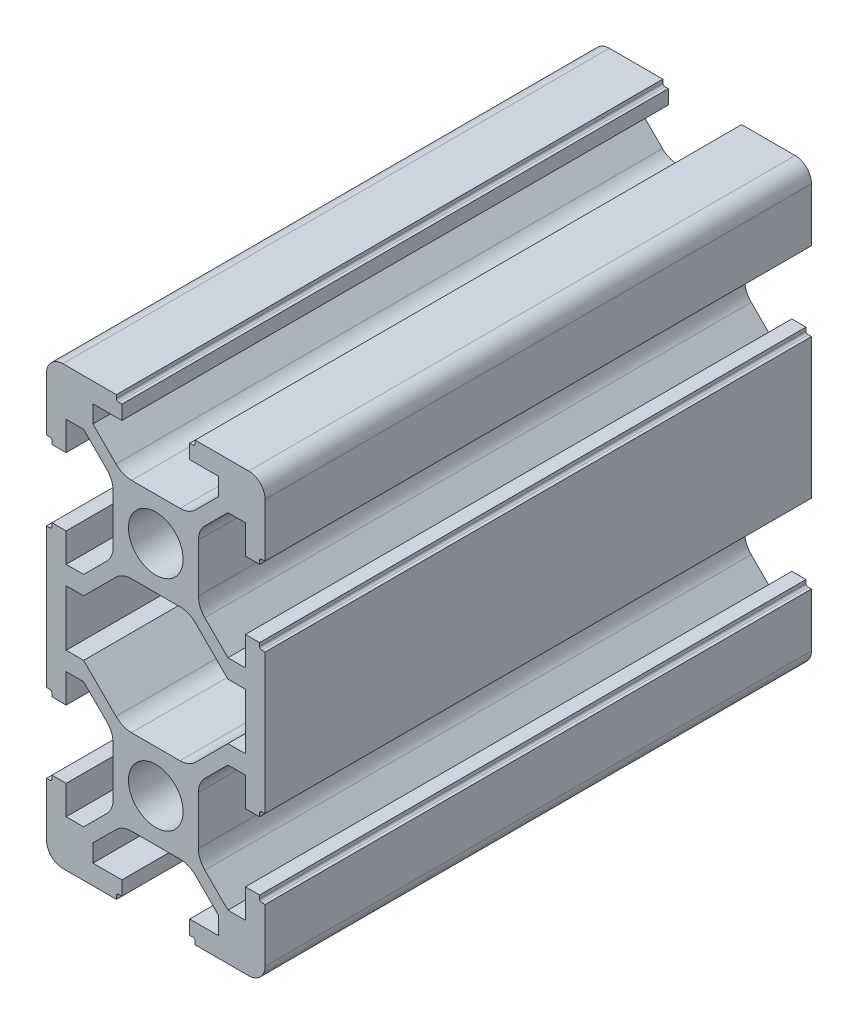
SolidWorks part; units mm, degrees
ref_plane "Alzado" through (0, 0, 0) normal (0, 0, 1) x (1, 0, 0)
ref_plane "Planta" through (0, 0, 0) normal (0, 1, 0) x (1, 0, 0)
ref_plane "Vista lateral" through (0, 0, 0) normal (1, 0, 0) x (0, 0, -1)
sketch "Croquis1" plane through (0, 0, 0) normal (0, 0, 1) x (1, 0, 0)
  line L0 (0, 0) -> (-10, -10) construction
  line L32 (0, 0) -> (-3.9, 0) construction
  line L58 (0, 0) -> (0, -3.9) construction
  line L60 (-4.4858, -3.6373) -> (-6.6, -5.7515)
  line L61 (-6.6, -5.7515) -> (-8.2, -5.7515)
  line L110 (-8.2, -5.7515) -> (-8.2, -3.1)
  line L111 (-8.2, -3.1) -> (-9.5, -3.1)
  line L112 (-9.5, -3.1) -> (-9.5, -3.4)
  line L113 (-9.7, -3.6) -> (-10, -3.6)
  line L114 (-10, -3.6) -> (-10, -8.5)
  line L115 (-3.6373, -4.4858) -> (-5.7515, -6.6)
  line L116 (-5.7515, -6.6) -> (-5.7515, -8.2)
  line L117 (-3.1, -8.2) -> (-3.1, -9.5)
  line L118 (-5.7515, -8.2) -> (-3.1, -8.2)
  line L119 (-3.1, -9.5) -> (-3.4, -9.5)
  line L120 (-3.6, -9.7) -> (-3.6, -10)
  line L121 (-3.6, -10) -> (-8.5, -10)
  line L122 (9.7, -3.6) -> (10, -3.6)
  line L123 (9.5, -3.1) -> (9.5, -3.4)
  line L124 (8.2, -3.1) -> (9.5, -3.1)
  line L125 (3.6, -10) -> (8.5, -10)
  line L126 (3.6, -9.7) -> (3.6, -10)
  line L127 (3.1, -9.5) -> (3.4, -9.5)
  line L128 (5.7515, -8.2) -> (3.1, -8.2)
  line L129 (3.1, -8.2) -> (3.1, -9.5)
  line L130 (5.7515, -6.6) -> (5.7515, -8.2)
  line L131 (3.6373, -4.4858) -> (5.7515, -6.6)
  line L132 (10, -3.6) -> (10, -8.5)
  line L133 (8.2, -5.7515) -> (8.2, -3.1)
  line L134 (6.6, -5.7515) -> (8.2, -5.7515)
  line L135 (4.4858, -3.6373) -> (6.6, -5.7515)
  line L136 (5.7515, 8.2) -> (3.1, 8.2)
  line L137 (3.6, 10) -> (8.5, 10)
  line L138 (-9.7, 3.6) -> (-10, 3.6)
  line L139 (-9.5, 3.1) -> (-9.5, 3.4)
  line L140 (-8.2, 3.1) -> (-9.5, 3.1)
  line L141 (-8.2, 5.7515) -> (-8.2, 3.1)
  line L142 (-6.6, 5.7515) -> (-8.2, 5.7515)
  line L143 (-4.4858, 3.6373) -> (-6.6, 5.7515)
  line L144 (3.1, 8.2) -> (3.1, 9.5)
  line L145 (3.1, 9.5) -> (3.4, 9.5)
  line L146 (3.6, 9.7) -> (3.6, 10)
  line L147 (-3.6, 10) -> (-8.5, 10)
  line L148 (-3.6, 9.7) -> (-3.6, 10)
  line L149 (-3.1, 9.5) -> (-3.4, 9.5)
  line L150 (-5.7515, 8.2) -> (-3.1, 8.2)
  line L151 (-3.1, 8.2) -> (-3.1, 9.5)
  line L152 (-5.7515, 6.6) -> (-5.7515, 8.2)
  line L153 (-3.6373, 4.4858) -> (-5.7515, 6.6)
  line L154 (-10, 3.6) -> (-10, 8.5)
  line L155 (4.4858, 3.6373) -> (6.6, 5.7515)
  line L156 (6.6, 5.7515) -> (8.2, 5.7515)
  line L157 (8.2, 5.7515) -> (8.2, 3.1)
  line L158 (10, 3.6) -> (10, 8.5)
  line L159 (3.6373, 4.4858) -> (5.7515, 6.6)
  line L160 (5.7515, 6.6) -> (5.7515, 8.2)
  line L161 (8.2, 3.1) -> (9.5, 3.1)
  line L162 (9.5, 3.1) -> (9.5, 3.4)
  line L163 (9.7, 3.6) -> (10, 3.6)
  line L164 (-3.9, 2.223) -> (-3.9, -2.223)
  line L165 (-2.223, -3.9) -> (2.223, -3.9)
  line L166 (3.9, -2.223) -> (3.9, 2.223)
  line L167 (2.223, 3.9) -> (-2.223, 3.9)
  circle A2 centre (0, 0) radius 2.5
  arc A3 (8.5, -10) -> (10, -8.5) centre (8.5, -8.5) ccw
  arc A4 (8.5, 10) -> (10, 8.5) centre (8.5, 8.5) cw
  arc A5 (-8.5, 10) -> (-10, 8.5) centre (-8.5, 8.5) ccw
  arc A6 (-10, -8.5) -> (-8.5, -10) centre (-8.5, -8.5) ccw
  arc A7 (-3.9, -2.223) -> (-4.4858, -3.6373) centre (-5.9, -2.223) cw
  arc A8 (4.4858, -3.6373) -> (3.9, -2.223) centre (5.9, -2.223) cw
  arc A9 (4.4858, 3.6373) -> (3.9, 2.223) centre (5.9, 2.223) ccw
  arc A10 (3.6373, 4.4858) -> (2.223, 3.9) centre (2.223, 5.9) cw
  arc A11 (-3.6373, 4.4858) -> (-2.223, 3.9) centre (-2.223, 5.9) ccw
  arc A12 (-4.4858, 3.6373) -> (-3.9, 2.223) centre (-5.9, 2.223) cw
  arc A13 (3.6373, -4.4858) -> (2.223, -3.9) centre (2.223, -5.9) ccw
  arc A14 (-3.6373, -4.4858) -> (-2.223, -3.9) centre (-2.223, -5.9) cw
  arc A15 (-3.4, -9.5) -> (-3.6, -9.7) centre (-3.4, -9.7) ccw
  arc A16 (3.6, -9.7) -> (3.4, -9.5) centre (3.4, -9.7) ccw
  arc A17 (9.7, -3.6) -> (9.5, -3.4) centre (9.7, -3.4) cw
  arc A18 (9.5, 3.4) -> (9.7, 3.6) centre (9.7, 3.4) cw
  arc A19 (3.4, 9.5) -> (3.6, 9.7) centre (3.4, 9.7) ccw
  arc A20 (-9.7, 3.6) -> (-9.5, 3.4) centre (-9.7, 3.4) cw
  arc A21 (-3.6, 9.7) -> (-3.4, 9.5) centre (-3.4, 9.7) ccw
  arc A22 (-9.5, -3.4) -> (-9.7, -3.6) centre (-9.7, -3.4) cw
  point P0 (0, 0)
  point P22 (10, -10)
  point P78 (10, 10)
  point P81 (-10, 10)
  point P90 (-3.9, -3.0515)
  point P93 (3.9, -3.0515)
  point P96 (3.9, 3.0515)
  point P99 (3.0515, 3.9)
  point P102 (-3.0515, 3.9)
  point P105 (-3.9, 3.0515)
  point P108 (3.0515, -3.9)
  point P111 (-3.0515, -3.9)
  point P116 (-3.6, -9.5)
  point P119 (3.6, -9.5)
  point P122 (9.5, -3.6)
  point P125 (9.5, 3.6)
  point P128 (3.6, 9.5)
  point P131 (-9.5, 3.6)
  point P134 (-3.6, 9.5)
  point P137 (-9.5, -3.6)
  dimension "D10" = 20
  dimension "D1" = 5
  dimension "D11" = 1.5
  dimension "D13" = 2
  dimension "D15" = 0.2
  dimension "D2" = 6.2
  dimension "D3" = 7.2
  dimension "D4" = 0.5
  dimension "D5" = 3.4
  dimension "D6" = 11.5029
  dimension "D7" = 6.1
  dimension "D8" = 1.8
  dimension "D9" = 1.2
extrude "Saliente-Extruir1" [suppressed] add sketch "Croquis1" along normal mid plane 100
sketch "Croquis3" plane through (0, 0, 0) normal (0, 0, 1) x (1, 0, 0)
  line L0 (-3.6363, -5.5152) -> (-6.6, -2.5556)
  line L3 (0, 0) -> (-10, 0) construction
  line L5 (-6.6, -2.5556) -> (-8.2, -2.5556)
  line L7 (0, -13.9) -> (0, -6.1) construction
  line L56 (-9.5, -13.1015) -> (-9.5, -13.4015)
  line L57 (-8.2, -13.1015) -> (-9.5, -13.1015)
  line L58 (-8.2, -15.7515) -> (-8.2, -13.1015)
  line L59 (-6.6, -15.7515) -> (-8.2, -15.7515)
  line L60 (-4.4858, -13.6373) -> (-6.6, -15.7515)
  line L61 (-3.9, -7.777) -> (-3.9, -12.223)
  line L62 (-6.6, -4.2515) -> (-4.4868, -6.3618)
  line L63 (-8.2, -4.2515) -> (-6.6, -4.2515)
  line L64 (-8.2, -6.9015) -> (-8.2, -4.2515)
  line L65 (-9.5, -6.9015) -> (-8.2, -6.9015)
  line L66 (-9.5, -6.6015) -> (-9.5, -6.9015)
  line L67 (-10, -6.4015) -> (-9.7, -6.4015)
  line L68 (-5.7515, -16.6) -> (-3.6373, -14.4858)
  line L69 (-5.7515, -18.2) -> (-5.7515, -16.6)
  line L70 (-3.1015, -18.2) -> (-5.7515, -18.2)
  line L71 (-3.1015, -19.5) -> (-3.1015, -18.2)
  line L72 (-3.4015, -19.5) -> (-3.1015, -19.5)
  line L73 (-3.6015, -20) -> (-3.6015, -19.7)
  line L74 (-8.5, -20) -> (-3.6015, -20)
  line L75 (-10, -13.6015) -> (-10, -18.5)
  line L76 (-9.7, -13.6015) -> (-10, -13.6015)
  line L102 (-10, -6.4015) -> (-10, 6.4015)
  line L103 (-8.2, -2.5556) -> (-8.2, 2.5556)
  line L104 (-2.223, -6.1) -> (2.223, -6.1)
  line L105 (-2.223, -13.9) -> (2.223, -13.9)
  line L106 (8.2, -2.5556) -> (8.2, 2.5556)
  line L107 (10, -6.4015) -> (10, 6.4015)
  line L108 (9.7, -13.6015) -> (10, -13.6015)
  line L109 (10, -13.6015) -> (10, -18.5)
  line L110 (8.5, -20) -> (3.6015, -20)
  line L111 (3.6015, -20) -> (3.6015, -19.7)
  line L112 (3.4015, -19.5) -> (3.1015, -19.5)
  line L113 (3.1015, -19.5) -> (3.1015, -18.2)
  line L114 (3.1015, -18.2) -> (5.7515, -18.2)
  line L115 (5.7515, -18.2) -> (5.7515, -16.6)
  line L116 (5.7515, -16.6) -> (3.6373, -14.4858)
  line L117 (10, -6.4015) -> (9.7, -6.4015)
  line L118 (9.5, -6.6015) -> (9.5, -6.9015)
  line L119 (9.5, -6.9015) -> (8.2, -6.9015)
  line L120 (8.2, -6.9015) -> (8.2, -4.2515)
  line L121 (8.2, -4.2515) -> (6.6, -4.2515)
  line L122 (6.6, -4.2515) -> (4.4868, -6.3618)
  line L123 (3.9, -7.777) -> (3.9, -12.223)
  line L124 (4.4858, -13.6373) -> (6.6, -15.7515)
  line L125 (6.6, -15.7515) -> (8.2, -15.7515)
  line L126 (8.2, -15.7515) -> (8.2, -13.1015)
  line L127 (8.2, -13.1015) -> (9.5, -13.1015)
  line L128 (9.5, -13.1015) -> (9.5, -13.4015)
  line L129 (6.6, -2.5556) -> (8.2, -2.5556)
  line L130 (3.6363, -5.5152) -> (6.6, -2.5556)
  line L131 (3.6363, 5.5152) -> (6.6, 2.5556)
  line L132 (6.6, 2.5556) -> (8.2, 2.5556)
  line L133 (9.5, 13.1015) -> (9.5, 13.4015)
  line L134 (8.2, 13.1015) -> (9.5, 13.1015)
  line L135 (8.2, 15.7515) -> (8.2, 13.1015)
  line L136 (6.6, 15.7515) -> (8.2, 15.7515)
  line L137 (4.4858, 13.6373) -> (6.6, 15.7515)
  line L138 (3.9, 7.777) -> (3.9, 12.223)
  line L139 (6.6, 4.2515) -> (4.4868, 6.3618)
  line L140 (8.2, 4.2515) -> (6.6, 4.2515)
  line L141 (8.2, 6.9015) -> (8.2, 4.2515)
  line L142 (9.5, 6.9015) -> (8.2, 6.9015)
  line L143 (9.5, 6.6015) -> (9.5, 6.9015)
  line L144 (10, 6.4015) -> (9.7, 6.4015)
  line L145 (5.7515, 16.6) -> (3.6373, 14.4858)
  line L146 (5.7515, 18.2) -> (5.7515, 16.6)
  line L147 (3.1015, 18.2) -> (5.7515, 18.2)
  line L148 (3.1015, 19.5) -> (3.1015, 18.2)
  line L149 (3.4015, 19.5) -> (3.1015, 19.5)
  line L150 (3.6015, 20) -> (3.6015, 19.7)
  line L151 (8.5, 20) -> (3.6015, 20)
  line L152 (10, 13.6015) -> (10, 18.5)
  line L153 (9.7, 13.6015) -> (10, 13.6015)
  line L154 (-2.223, 13.9) -> (2.223, 13.9)
  line L155 (-2.223, 6.1) -> (2.223, 6.1)
  line L156 (-9.7, 13.6015) -> (-10, 13.6015)
  line L157 (-10, 13.6015) -> (-10, 18.5)
  line L158 (-8.5, 20) -> (-3.6015, 20)
  line L159 (-3.6015, 20) -> (-3.6015, 19.7)
  line L160 (-3.4015, 19.5) -> (-3.1015, 19.5)
  line L161 (-3.1015, 19.5) -> (-3.1015, 18.2)
  line L162 (-3.1015, 18.2) -> (-5.7515, 18.2)
  line L163 (-5.7515, 18.2) -> (-5.7515, 16.6)
  line L164 (-5.7515, 16.6) -> (-3.6373, 14.4858)
  line L165 (-10, 6.4015) -> (-9.7, 6.4015)
  line L166 (-9.5, 6.6015) -> (-9.5, 6.9015)
  line L167 (-9.5, 6.9015) -> (-8.2, 6.9015)
  line L168 (-8.2, 6.9015) -> (-8.2, 4.2515)
  line L169 (-8.2, 4.2515) -> (-6.6, 4.2515)
  line L170 (-6.6, 4.2515) -> (-4.4868, 6.3618)
  line L171 (-3.9, 7.777) -> (-3.9, 12.223)
  line L172 (-4.4858, 13.6373) -> (-6.6, 15.7515)
  line L173 (-6.6, 15.7515) -> (-8.2, 15.7515)
  line L174 (-8.2, 15.7515) -> (-8.2, 13.1015)
  line L175 (-8.2, 13.1015) -> (-9.5, 13.1015)
  line L176 (-9.5, 13.1015) -> (-9.5, 13.4015)
  line L177 (-6.6, 2.5556) -> (-8.2, 2.5556)
  line L178 (-3.6363, 5.5152) -> (-6.6, 2.5556)
  line L179 (0, -10) -> (-9.5607, -19.5607) construction
  circle A8 centre (0, -10) radius 2.5
  arc A20 (-4.4858, -13.6373) -> (-3.9, -12.223) centre (-5.9, -12.223) ccw
  arc A21 (-3.9, -7.777) -> (-4.4868, -6.3618) centre (-5.9, -7.777) ccw
  arc A22 (-9.5, -6.6015) -> (-9.7, -6.4015) centre (-9.7, -6.6015) ccw
  arc A23 (-3.6363, -5.5152) -> (-2.223, -6.1) centre (-2.223, -4.1) ccw
  arc A24 (-2.223, -13.9) -> (-3.6373, -14.4858) centre (-2.223, -15.9) ccw
  arc A25 (-3.4015, -19.5) -> (-3.6015, -19.7) centre (-3.4015, -19.7) ccw
  arc A26 (-10, -18.5) -> (-8.5, -20) centre (-8.5, -18.5) ccw
  arc A27 (-9.7, -13.6015) -> (-9.5, -13.4015) centre (-9.7, -13.4015) ccw
  arc A34 (9.7, -13.6015) -> (9.5, -13.4015) centre (9.7, -13.4015) cw
  arc A35 (10, -18.5) -> (8.5, -20) centre (8.5, -18.5) cw
  arc A36 (3.4015, -19.5) -> (3.6015, -19.7) centre (3.4015, -19.7) cw
  arc A37 (2.223, -13.9) -> (3.6373, -14.4858) centre (2.223, -15.9) cw
  arc A38 (3.6363, -5.5152) -> (2.223, -6.1) centre (2.223, -4.1) cw
  arc A39 (9.5, -6.6015) -> (9.7, -6.4015) centre (9.7, -6.6015) cw
  arc A40 (3.9, -7.777) -> (4.4868, -6.3618) centre (5.9, -7.777) cw
  arc A41 (4.4858, -13.6373) -> (3.9, -12.223) centre (5.9, -12.223) cw
  arc A42 (4.4858, 13.6373) -> (3.9, 12.223) centre (5.9, 12.223) ccw
  arc A43 (3.9, 7.777) -> (4.4868, 6.3618) centre (5.9, 7.777) ccw
  arc A44 (9.5, 6.6015) -> (9.7, 6.4015) centre (9.7, 6.6015) ccw
  arc A45 (3.6363, 5.5152) -> (2.223, 6.1) centre (2.223, 4.1) ccw
  arc A46 (2.223, 13.9) -> (3.6373, 14.4858) centre (2.223, 15.9) ccw
  arc A47 (3.4015, 19.5) -> (3.6015, 19.7) centre (3.4015, 19.7) ccw
  arc A48 (10, 18.5) -> (8.5, 20) centre (8.5, 18.5) ccw
  arc A49 (9.7, 13.6015) -> (9.5, 13.4015) centre (9.7, 13.4015) ccw
  arc A50 (-9.7, 13.6015) -> (-9.5, 13.4015) centre (-9.7, 13.4015) cw
  arc A51 (-10, 18.5) -> (-8.5, 20) centre (-8.5, 18.5) cw
  arc A52 (-3.4015, 19.5) -> (-3.6015, 19.7) centre (-3.4015, 19.7) cw
  arc A53 (-2.223, 13.9) -> (-3.6373, 14.4858) centre (-2.223, 15.9) cw
  arc A54 (-3.6363, 5.5152) -> (-2.223, 6.1) centre (-2.223, 4.1) cw
  arc A55 (-9.5, 6.6015) -> (-9.7, 6.4015) centre (-9.7, 6.6015) cw
  arc A56 (-3.9, 7.777) -> (-4.4868, 6.3618) centre (-5.9, 7.777) cw
  arc A57 (-4.4858, 13.6373) -> (-3.9, 12.223) centre (-5.9, 12.223) cw
  circle A58 centre (0, 10) radius 2.5
  point P59 (8.2, 0)
  point P63 (8.2, 0)
  point P159 (10, 0)
  point P160 (-8.2, 0)
  point P174 (-8.2, 0)
  point P190 (-3.9, -10)
  point P193 (0, -10)
  dimension "D8" = 2
  dimension "D9" = 1.5
  dimension "D11" = 5
  dimension "D13" = 0.2
  dimension "D1" = 40
  dimension "D2" = 11.5
  dimension "D3" = 6.2
  dimension "D4" = 1.8
  dimension "D5" = 0.5
  dimension "D6" = 3.4
  dimension "D7" = 20
  dimension "D10" = 1.2
  dimension "D12" = 7.8
  dimension "D14" = 20
extrude "Saliente-Extruir3" add sketch "Croquis3" along normal mid plane 350 separate body
sketch "Sketch1" plane through (0, 20, 0) normal (0, 1, 0) x (1, 0, 0)
  line L0 (10, 175) -> (8.5, 175) construction
  line L1 (8.5, -175) -> (10, -175) construction
  line L2 (10, -175) -> (10, 175) construction
  line L3 (8.5, 175) -> (3.6015, 175) construction
  line L4 (3.6015, 175) -> (3.6015, -175) construction
  line L5 (3.6015, -175) -> (8.5, -175) construction
  line L6 (3.6373, 175) -> (2.223, 175) construction
  line L7 (2.223, -175) -> (3.6373, -175) construction
  line L8 (3.6373, -175) -> (3.6373, 175) construction
  line L10 (-2.223, -175) -> (2.223, -175) construction
  line L11 (-2.223, 175) -> (-3.6373, 175) construction
  line L12 (-3.6373, 175) -> (-3.6373, -175) construction
  line L13 (-3.6373, -175) -> (-2.223, -175) construction
  line L14 (-3.6015, 175) -> (-8.5, 175) construction
  line L15 (-8.5, -175) -> (-3.6015, -175) construction
  line L16 (-3.6015, -175) -> (-3.6015, 175) construction
  line L17 (-8.5, 175) -> (-10, 175) construction
  line L18 (-10, 175) -> (-10, -175) construction
  line L19 (-10, -175) -> (-8.5, -175) construction
  line L20 (10, 175) -> (8.5, 175)
  line L21 (8.5, -175) -> (10, -175)
  line L22 (10, -175) -> (10, 125)
  line L23 (3.6373, 175) -> (3.6015, 175)
  line L24 (3.6015, 125) -> (3.6015, -175)
  line L25 (3.6015, -175) -> (8.5, -175)
  line L26 (3.6373, 175) -> (2.223, 175)
  line L27 (2.223, -175) -> (3.6373, -175)
  line L28 (3.6373, -175) -> (3.6373, 125)
  line L30 (-2.223, -175) -> (2.223, -175)
  line L31 (-3.6015, 175) -> (-3.6373, 175)
  line L32 (-3.6373, 125) -> (-3.6373, -175)
  line L33 (-3.6373, -175) -> (-2.223, -175)
  line L34 (-3.6015, 175) -> (-3.6373, 175)
  line L35 (-8.5, -175) -> (-3.6015, -175)
  line L36 (-3.6015, -175) -> (-3.6015, 125)
  line L37 (-8.5, 175) -> (-10, 175)
  line L38 (-10, 125) -> (-10, -175)
  line L39 (-10, -175) -> (-8.5, -175)
  line L40 (-10, 125) -> (10, 125)
  line L41 (10, 125) -> (10, -175)
  line L42 (10, -175) -> (8.5, -175)
  line L43 (10, -175) -> (-10, -175)
  line L44 (-10, -175) -> (-10, 125)
  line M6 (-8.5, 175) -> (-8.5, -175)
  line M7 (-8.5, -175) -> (-3.6015, -175)
  line M8 (-3.6015, -175) -> (-3.6015, 175)
  dimension "D1" = 350
  dimension "D2" = 300
extrude "Cut-Extrude3" cut sketch "Sketch1" against normal blind 100 contours L40 L28 L25 L21 L22 | L40 L33 L30 L27 L24 M8 | L40 L32 M6 M7 | L40 L38 L39 M6 | L40 L32 M7 M8 | L40 L24 L25 L28
sketch "Sketch2" plane through (10, 0, 0) normal (1, 0, 0) x (0, 0, -1)
  line L8 (125, 6.4015) -> (125, -6.4015) construction
  line L9 (125, -6.4015) -> (175, -6.4015) construction
  line L10 (175, -6.4015) -> (175, 6.4015) construction
  line L11 (175, 6.4015) -> (125, 6.4015) construction
  line L12 (125, 20) -> (125, 18.5)
  line L14 (175, 18.5) -> (175, 20)
  line L16 (125, -18.5) -> (125, -20)
  line L18 (175, -20) -> (175, -18.5)
  line L20 (125, 6.4015) -> (125, -6.4015)
  line L21 (125, -6.4015) -> (175, -6.4015)
  line L22 (175, -6.4015) -> (175, 6.4015)
  line L23 (175, 6.4015) -> (125, 6.4015)
  line L24 (125, 18.5) -> (125, -18.2)
  line L25 (175, 18.5) -> (175, -18.5)
  line L26 (125, 20) -> (125, -20)
  line L27 (125, 0) -> (175, 0) construction
  line L28 (125, -20) -> (175, -20)
  line L29 (150, 20) -> (150, -20) construction
  line L30 (125, 18.5) -> (175, 18.5) construction
  line L31 (125, 20) -> (175, 20) construction
  line L32 (125, 18.5) -> (175, 18.5)
  line L33 (125, 20) -> (175, 20)
  line L34 (125, -20) -> (175, -20) construction
  line L35 (125, -18.5) -> (175, -18.5) construction
  line L36 (125, -20) -> (175, -20)
  line L37 (125, -18.5) -> (175, -18.5)
  circle A0 centre (137.5, 10) radius 3
  circle A1 centre (162.5, 10) radius 3
  circle A2 centre (162.5, -10) radius 3
  circle A3 centre (137.5, -10) radius 3
  point P21 (137.5, 10)
  point P23 (162.5, 10)
  point P25 (162.5, -10)
  point P27 (137.5, -10)
  dimension "D3" = 6
  dimension "D1" = 50
  dimension "D2" = 25
  dimension "D5" = 12.5
  dimension "D6" = 50
hole_wizard "Ø6.0mm Dowel Hole1" [suppressed] positions "Sketch2" profile "Sketch4" hole size "Ø6.0" standard "ANSI Metric"
sketch "Sketch4" plane through (10, -10, -137.5) normal (0, 1, 0) x (0, 0, -1)
  line L0 (0, 0) -> (0, 20)
  line L1 (0, 20) -> (3, 20)
  line L2 (3, 20) -> (3, 0)
  line L5 (3, 0) -> (0, 0)
  line L11 (0, -6.35) -> (0, 107.95) construction
  dimension "Thru Hole Dia." = 6
  dimension "Thru Hole Depth" = 20
